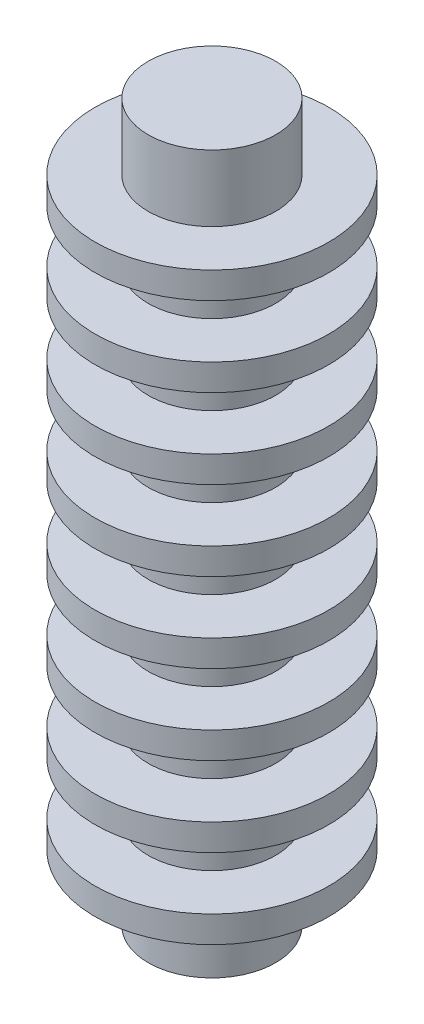
SolidWorks part; units mm, degrees
ref_plane "Front Plane" through (0, 0, 0) normal (0, 0, 1) x (1, 0, 0)
ref_plane "Top Plane" through (0, 0, 0) normal (0, 1, 0) x (1, 0, 0)
ref_plane "Right Plane" through (0, 0, 0) normal (1, 0, 0) x (0, 0, -1)
sketch "Sketch1" plane through (0, 0, 0) normal (0, 0, 1) x (1, 0, 0)
  line L0 (0, -24) -> (0, 24) construction
  line L1 (4.8, 24) -> (4.8, 22)
  line L2 (-18.9325, 24) -> (4.8, 24) construction
  line L3 (4.8, 18) -> (4.8, 16)
  line L4 (4.8, 16) -> (8.8, 16)
  line L5 (4.8, 22) -> (8.8, 22)
  line L6 (8.8, 22) -> (8.8, 20)
  line L7 (8.8, 20) -> (4.8, 20)
  line L8 (4.8, 20) -> (4.8, 18)
  line L9 (4.8, 24) -> (4.8, 27)
  line L10 (4.8, 27) -> (0, 27)
  line L11 (4.8, -24) -> (4.8, -27)
  line L12 (4.8, -27) -> (0, -27)
  line L13 (8.8, 16) -> (8.8, 14)
  line L14 (8.8, 14) -> (4.8, 14)
  line L15 (4.8, 14) -> (4.8, 11)
  line L16 (0, 27) -> (0, -27)
  line L20 (4.8, 11) -> (4.8, 10)
  line L21 (4.8, 10) -> (8.8, 10)
  line L22 (8.8, 10) -> (8.8, 8)
  line L23 (8.8, 8) -> (4.8, 8)
  line L24 (4.8, 8) -> (4.8, 5)
  line L29 (4.8, 5) -> (4.8, 4)
  line L30 (4.8, 4) -> (8.8, 4)
  line L31 (8.8, 4) -> (8.8, 2)
  line L32 (8.8, 2) -> (4.8, 2)
  line L33 (4.8, 2) -> (4.8, -1)
  line L38 (4.8, -1) -> (4.8, -2)
  line L39 (4.8, -2) -> (8.8, -2)
  line L40 (8.8, -2) -> (8.8, -4)
  line L41 (8.8, -4) -> (4.8, -4)
  line L42 (4.8, -4) -> (4.8, -7)
  line L47 (4.8, -7) -> (4.8, -8)
  line L48 (4.8, -8) -> (8.8, -8)
  line L49 (8.8, -8) -> (8.8, -10)
  line L50 (8.8, -10) -> (4.8, -10)
  line L51 (4.8, -10) -> (4.8, -13)
  line L56 (4.8, -13) -> (4.8, -14)
  line L57 (4.8, -14) -> (8.8, -14)
  line L58 (8.8, -14) -> (8.8, -16)
  line L59 (8.8, -16) -> (4.8, -16)
  line L60 (4.8, -16) -> (4.8, -19)
  line L65 (4.8, -19) -> (4.8, -20)
  line L66 (4.8, -20) -> (8.8, -20)
  line L67 (8.8, -20) -> (8.8, -22)
  line L68 (8.8, -22) -> (4.8, -22)
  line L69 (4.8, -22) -> (4.8, -24)
  point P3 (4.8, 20)
  point P4 (0, 0)
  dimension "D1" = 48
  dimension "D2" = 4.8
  dimension "D3" = 3
  dimension "D4" = 3
  dimension "D5" = 2
  dimension "D6" = 2
  dimension "D7" = 4
  dimension "D8" = 2
  dimension "D9" = 2
  dimension "D10" = 2
  dimension "D11" = 2
  dimension "D12" = 2
  dimension "D13" = 2
  dimension "D14" = 2
  dimension "D15" = 2
  dimension "D16" = 4
  dimension "D17" = 4
  dimension "D18" = 4
  dimension "D19" = 4
  dimension "D20" = 4
  dimension "D21" = 4
  dimension "D22" = 4
  dimension "D23" = 54
  dimension "D24" = 4
  dimension "D25" = 4
  dimension "D26" = 4
  dimension "D27" = 4
  dimension "D28" = 4
  dimension "D29" = 4
  dimension "D30" = 4
  dimension "D31" = 4
  dimension "D32" = 4.8
revolve "Revolve1" add sketch "Sketch1" angle 360 about L16
